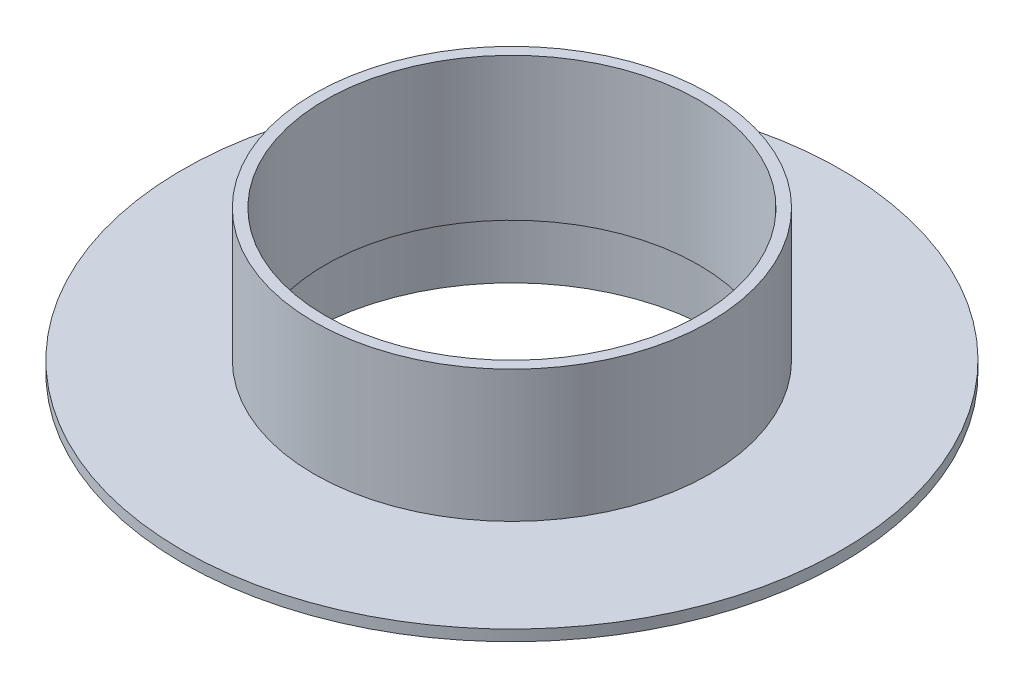
SolidWorks part; units mm, degrees
ref_plane "前视基准面" through (0, 0, 0) normal (0, 0, 1) x (1, 0, 0)
ref_plane "上视基准面" through (0, 0, 0) normal (0, 1, 0) x (1, 0, 0)
ref_plane "右视基准面" through (0, 0, 0) normal (1, 0, 0) x (0, 0, -1)
sketch "草图2" plane through (0, 0, 0) normal (0, 1, 0) x (1, 0, 0)
  circle A0 centre (0, 0) radius 150
  dimension "D1" = 300
extrude "凸台-拉伸1" add sketch "草图2" along normal blind 5
sketch "草图3" plane through (0, 5, 0) normal (0, 1, 0) x (1, 0, 0)
  circle A0 centre (0, 0) radius 90
  dimension "D1" = 180
extrude "凸台-拉伸2" add sketch "草图3" along normal blind 60
sketch "草图4" plane through (0, 0, 0) normal (0, -1, 0) x (1, 0, 0)
  circle A2 centre (0, 0) radius 85
extrude "切除-拉伸1" cut sketch "草图4" against normal through all
sketch "草图5" plane through (0, 0, 0) normal (0, -1, 0) x (1, 0, 0)
  circle A2 centre (0, 0) radius 97.5
  circle A3 centre (0, 0) radius 92.5
  circle M1 centre (0, 0) radius 85
  dimension "D1" = 195
  dimension "D2" = 185
extrude "凸台-拉伸3" add sketch "草图5" along normal blind 30 contours A2 M1
sketch "草图7" plane through (0, -30, 0) normal (0, -1, 0) x (1, 0, 0)
  circle A0 centre (0, 0) radius 150
  dimension "D1" = 300
extrude "切除-拉伸6" [suppressed] cut sketch "草图7" against normal up to surface (30 mm away)
sketch "草图8" plane through (0, 65, 0) normal (0, 1, 0) x (1, 0, 0)
  circle A0 centre (0, 0) radius 150
extrude "切除-拉伸7" [suppressed] cut sketch "草图8" against normal up to surface (60 mm away)
sketch "草图9" plane through (0, 0, 0) normal (0, -1, 0) x (1, 0, 0)
  circle A1 centre (0, 0) radius 92.5
  circle A4 centre (0, 0) radius 92.5
  dimension "D1" = 0
extrude "切除-拉伸8" [suppressed] cut sketch "草图9" against normal blind 10
